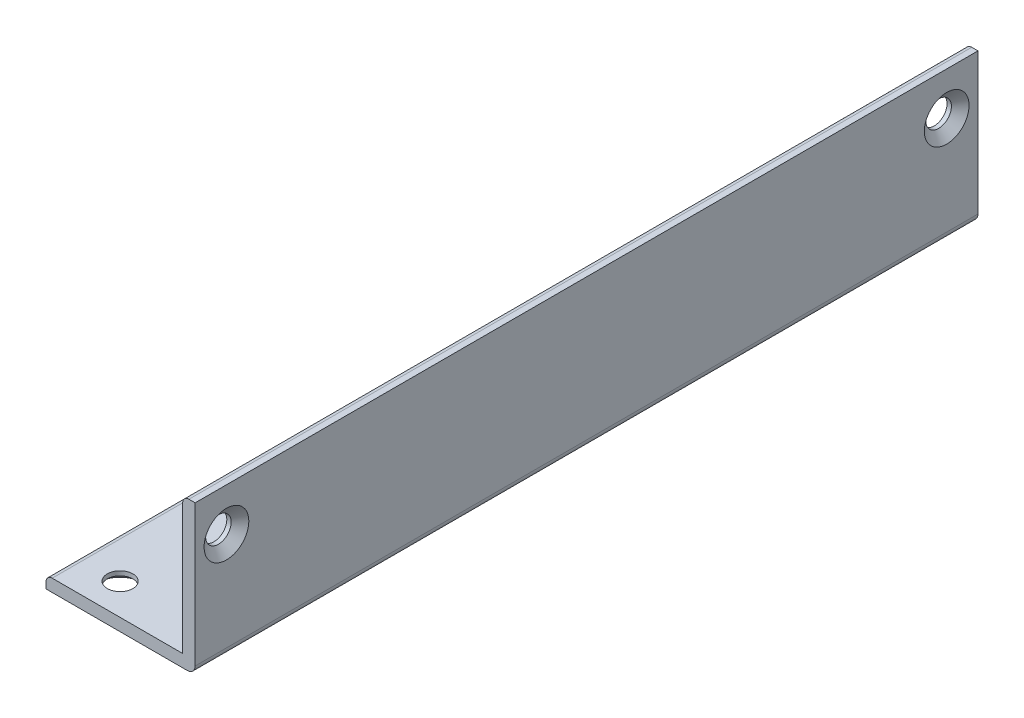
SolidWorks part; units mm, degrees
material "6061-T6 (SS)"
ref_plane "Front Plane" through (0, 0, 0) normal (0, 0, 1) x (1, 0, 0)
ref_plane "Top Plane" through (0, 0, 0) normal (0, 1, 0) x (1, 0, 0)
ref_plane "Right Plane" through (0, 0, 0) normal (1, 0, 0) x (0, 0, -1)
sketch "Sketch2" plane through (0, 0, 0) normal (0, 0, 1) x (1, 0, 0)
  line L0 (-9.525, 0) -> (9.525, 0)
  line L1 (9.525, 0) -> (9.525, 19.05)
  line L2 (9.525, 19.05) -> (7.9375, 19.05) construction
  line L3 (7.9375, 18.2563) -> (7.9375, 2.3812)
  line L4 (7.1438, 1.5875) -> (-8.7313, 1.5875)
  line L5 (-9.525, 0) -> (-9.525, 1.5875) construction
  line L6 (8.7313, 19.05) -> (9.525, 19.05)
  line L7 (-9.525, 0.7937) -> (-9.525, 0)
  arc A0 (7.9375, 18.2563) -> (8.7313, 19.05) centre (8.7313, 18.2563) cw
  arc A1 (-9.525, 0.7937) -> (-8.7313, 1.5875) centre (-8.7313, 0.7937) cw
  arc A2 (7.9375, 2.3812) -> (7.1438, 1.5875) centre (7.1438, 2.3812) cw
  dimension "Vert" = 19.05
  dimension "Horz" = 19.05
  dimension "Thickness" = 1.5875
extrude "Boss-Extrude1" add sketch "Sketch2" along normal mid plane 100
ref_plane "Contact Plane 1" through (0, 1.5875, 0) normal (0, 1, 0) x (1, 0, 0)
ref_plane "Contact Plane 2" through (7.9375, 0, 0) normal (-1, 0, 0) x (0, 0, 1)
sketch "Sketch6" plane through (0, 0, 0) normal (0, -1, 0) x (1, 0, 0)
  line L0 (9.525, 46) -> (-4.0625, 46) construction
  line L1 (9.525, 50) -> (9.525, -50) construction
  line L2 (-9.525, 50) -> (9.525, 50) construction
  line L3 (9.525, 0) -> (-9.525, 0) construction
  line L4 (-9.525, 50) -> (-9.525, -50) construction
  point P7 (-4.0625, 46)
  point P11 (-4.0625, -46)
  dimension "D1" = 4
  dimension "D2" = 13.5875
hole_wizard "CSK for #4 Flat Head Machine Screw (100)1" positions "Sketch7" profile "Sketch8" countersink size "#4" standard "ANSI Inch" end condition through all
sketch "Sketch7" plane through (0, 0, 0) normal (0, -1, 0) x (-1, 0, 0)
  point P0 (4.0625, -46)
  point P3 (4.0625, 46)
sketch "Sketch8" plane through (-4.0625, 0, 46) normal (1, 0, 0) x (0, 0, -1)
  line L0 (0, 0) -> (0, 19.05)
  line L1 (0, 19.05) -> (1.6319, 19.05)
  line L2 (1.6319, 19.05) -> (1.6319, 1.0284)
  line L3 (1.6319, 1.0284) -> (2.8575, 0)
  line L5 (2.8575, 0) -> (0, 0)
  line L6 (-1.6319, 1.0284) -> (-2.8575, 0) construction
  line L11 (0, -6.35) -> (0, 107.95) construction
  dimension "Thru Hole Dia." = 3.2639
  dimension "Thru Hole Depth" = 19.05
  dimension "Near C'Sink Dia." = 5.715
  dimension "Near C'Sink Angle" = 100
sketch "Sketch9" plane through (9.525, 0, 0) normal (1, 0, 0) x (0, 0, -1)
  line L0 (-46, 0) -> (-46, 13.5875) construction
  line L1 (0, 0) -> (0, 19.05) construction
  line L2 (-50, 0) -> (50, 0) construction
  line L3 (-50, 19.05) -> (50, 19.05) construction
  point P4 (-46, 13.5875)
  point P10 (46, 13.5875)
  dimension "D1" = 13.5875
hole_wizard "CSK for #4 Flat Head Machine Screw (100)2" positions "Sketch10" profile "Sketch11" countersink size "#4" standard "ANSI Inch" end condition through all
sketch "Sketch10" plane through (9.525, 0, 0) normal (1, 0, 0) x (0, 0, -1)
  point P0 (-46, 13.5875)
  point P3 (46, 13.5875)
sketch "Sketch11" plane through (9.525, 13.5875, 46) normal (0, 1, 0) x (0, 0, -1)
  line L0 (0, 0) -> (0, 19.05)
  line L1 (0, 19.05) -> (1.6319, 19.05)
  line L2 (1.6319, 19.05) -> (1.6319, 1.0284)
  line L3 (1.6319, 1.0284) -> (2.8575, 0)
  line L5 (2.8575, 0) -> (0, 0)
  line L6 (-1.6319, 1.0284) -> (-2.8575, 0) construction
  line L11 (0, -6.35) -> (0, 107.95) construction
  dimension "Thru Hole Dia." = 3.2639
  dimension "Thru Hole Depth" = 19.05
  dimension "Near C'Sink Dia." = 5.715
  dimension "Near C'Sink Angle" = 100
fillet "Fillet1" radius 1 1 edges at (9.525, 0, 0)
sketch "Sketch12" plane through (0, 0, 0) normal (0, -1, 0) x (1, 0, 0)
  line L0 (-4.0625, -50) -> (-4.0625, 50) construction
  line L1 (-9.525, -50) -> (8.525, -50) construction
  point P0 (-4.0625, -46)
  point P7 (-4.0625, 50)
  dimension "D1" = 100
hole_wizard "CSK for #4 Flat Head Machine Screw (100)3" positions "Sketch13" profile "Sketch14" countersink size "#4" standard "ANSI Inch"
sketch "Sketch13" plane through (0, 0, 0) normal (0, -1, 0) x (-1, 0, 0)
  point P0 (4.0625, 0)
sketch "Sketch14" plane through (-4.0625, 0, 0) normal (1, 0, 0) x (0, 0, -1)
  line L0 (0, 0) -> (0, 19.05)
  line L1 (0, 19.05) -> (1.6319, 19.05)
  line L2 (1.6319, 19.05) -> (1.6319, 1.0284)
  line L3 (1.6319, 1.0284) -> (2.8575, 0)
  line L5 (2.8575, 0) -> (0, 0)
  line L6 (-1.6319, 1.0284) -> (-2.8575, 0) construction
  line L11 (0, -6.35) -> (0, 107.95) construction
  dimension "Thru Hole Dia." = 3.2639
  dimension "Thru Hole Depth" = 19.05
  dimension "Near C'Sink Dia." = 5.715
  dimension "Near C'Sink Angle" = 100
sketch "Sketch15" plane through (9.525, 0, 0) normal (1, 0, 0) x (0, 0, -1)
  line L0 (50, 13.5875) -> (-50, 13.5875) construction
  line L1 (50, 1) -> (50, 19.05) construction
  point P0 (46, 13.5875)
  point P7 (-50, 13.5875)
  dimension "D1" = 100
hole_wizard "CSK for #4 Flat Head Machine Screw (100)4" positions "Sketch16" profile "Sketch17" countersink size "#4" standard "ANSI Inch"
sketch "Sketch16" plane through (9.525, 0, 0) normal (1, 0, 0) x (0, 0, -1)
  point P0 (0, 13.5875)
sketch "Sketch17" plane through (9.525, 13.5875, 0) normal (0, 1, 0) x (0, 0, -1)
  line L0 (0, 0) -> (0, 19.05)
  line L1 (0, 19.05) -> (1.6319, 19.05)
  line L2 (1.6319, 19.05) -> (1.6319, 1.0284)
  line L3 (1.6319, 1.0284) -> (2.8575, 0)
  line L5 (2.8575, 0) -> (0, 0)
  line L6 (-1.6319, 1.0284) -> (-2.8575, 0) construction
  line L11 (0, -6.35) -> (0, 107.95) construction
  dimension "Thru Hole Dia." = 3.2639
  dimension "Thru Hole Depth" = 19.05
  dimension "Near C'Sink Dia." = 5.715
  dimension "Near C'Sink Angle" = 100
sketch "Sketch18" plane through (9.525, 0, 0) normal (1, 0, 0) x (0, 0, -1)
  line L0 (-50, 13.5875) -> (-150, 13.5875) construction
  point P4 (-150, 13.5875)
  dimension "D1" = 100
hole_wizard "CSK for #4 Flat Head Machine Screw (100)5" positions "Sketch19" profile "Sketch20" countersink size "#4" standard "ANSI Inch"
sketch "Sketch19" plane through (9.525, 0, 0) normal (1, 0, 0) x (0, 0, -1)
  point P0 (-50, 13.5875)
sketch "Sketch20" plane through (9.525, 13.5875, 50) normal (0, 1, 0) x (0, 0, -1)
  line L0 (0, 0) -> (0, 19.05)
  line L1 (0, 19.05) -> (1.6319, 19.05)
  line L2 (1.6319, 19.05) -> (1.6319, 1.0284)
  line L3 (1.6319, 1.0284) -> (2.8575, 0)
  line L5 (2.8575, 0) -> (0, 0)
  line L6 (-1.6319, 1.0284) -> (-2.8575, 0) construction
  line L11 (0, -6.35) -> (0, 107.95) construction
  dimension "Thru Hole Dia." = 3.2639
  dimension "Thru Hole Depth" = 19.05
  dimension "Near C'Sink Dia." = 5.715
  dimension "Near C'Sink Angle" = 100
sketch "Sketch21" plane through (0, 0, 0) normal (0, -1, 0) x (1, 0, 0)
  line L0 (-4.0625, 50) -> (-4.0625, 150) construction
  point P4 (-4.0625, 150)
  dimension "D1" = 100
hole_wizard "CSK for #4 Flat Head Machine Screw (100)6" positions "Sketch22" profile "Sketch23" countersink size "#4" standard "ANSI Inch"
sketch "Sketch22" plane through (0, 0, 0) normal (0, -1, 0) x (-1, 0, 0)
  point P0 (4.0625, -50)
sketch "Sketch23" plane through (-4.0625, 0, 50) normal (1, 0, 0) x (0, 0, -1)
  line L0 (0, 0) -> (0, 19.05)
  line L1 (0, 19.05) -> (1.6319, 19.05)
  line L2 (1.6319, 19.05) -> (1.6319, 1.0284)
  line L3 (1.6319, 1.0284) -> (2.8575, 0)
  line L5 (2.8575, 0) -> (0, 0)
  line L6 (-1.6319, 1.0284) -> (-2.8575, 0) construction
  line L11 (0, -6.35) -> (0, 107.95) construction
  dimension "Thru Hole Dia." = 3.2639
  dimension "Thru Hole Depth" = 19.05
  dimension "Near C'Sink Dia." = 5.715
  dimension "Near C'Sink Angle" = 100
sketch "Sketch24" plane through (0, 0, 50) normal (0, 0, 1) x (1, 0, 0)
  line L0 (2.9375, 1.5875) -> (7.9375, 6.5875)
  line L1 (7.1438, 1.5875) -> (-8.7313, 1.5875) construction
  line L2 (7.9375, 18.2563) -> (7.9375, 2.3812) construction
  line L3 (7.9375, 6.5875) -> (7.9375, 1.5875)
  line L5 (2.9375, 1.5875) -> (7.9375, 1.5875)
  dimension "D1" = 5
  dimension "D2" = 5
extrude "Cut-Extrude1" cut sketch "Sketch24" against normal blind 25
ref_plane "Plane1" through (0, 0, 0) normal (0, 0, 1) x (1, 0, 0)
mirror "Mirror1" about plane through (0, 0, 0) normal (0, 0, 1) of "Cut-Extrude1"
